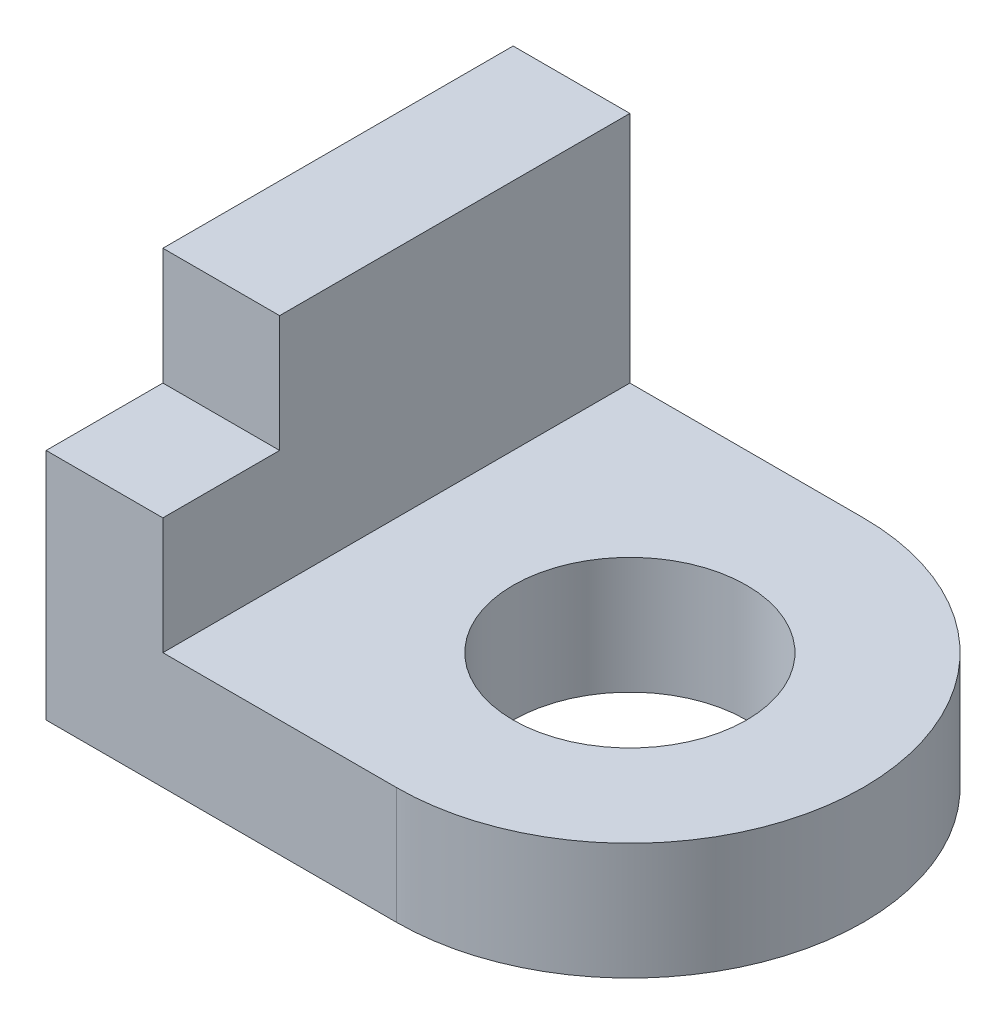
SolidWorks part; units mm, degrees
ref_plane "Front Plane" through (0, 0, 0) normal (0, 0, 1) x (1, 0, 0)
ref_plane "Top Plane" through (0, 0, 0) normal (0, 1, 0) x (1, 0, 0)
ref_plane "Right Plane" through (0, 0, 0) normal (1, 0, 0) x (0, 0, -1)
sketch "Sketch1" plane through (0, 0, 0) normal (0, 1, 0) x (1, 0, 0)
  line L0 (0, 20) -> (-30, 20)
  line L1 (-30, 20) -> (-30, -20)
  line L2 (-30, -20) -> (0, -20)
  circle A0 centre (0, 0) radius 10
  arc A1 (0, -20) -> (0, 20) centre (0, 0) ccw
  dimension "D1" = 20
  dimension "D2" = 40
  dimension "D3" = 30
extrude "Boss-Extrude1" add sketch "Sketch1" along normal blind 10
sketch "Sketch2" plane through (-30, 0, 0) normal (-1, 0, 0) x (0, 0, 1)
  line L0 (-20, 10) -> (-20, 30)
  line L1 (-20, 30) -> (10, 30)
  line L2 (10, 30) -> (10, 20)
  line L3 (10, 20) -> (20, 20)
  line L4 (20, 20) -> (20, 10)
  line L5 (20, 10) -> (-20, 10)
  dimension "D1" = 10
  dimension "D2" = 10
  dimension "D3" = 20
extrude "Boss-Extrude2" add sketch "Sketch2" against normal blind 10 contours L4 L5 L0 L1 L2 L3
